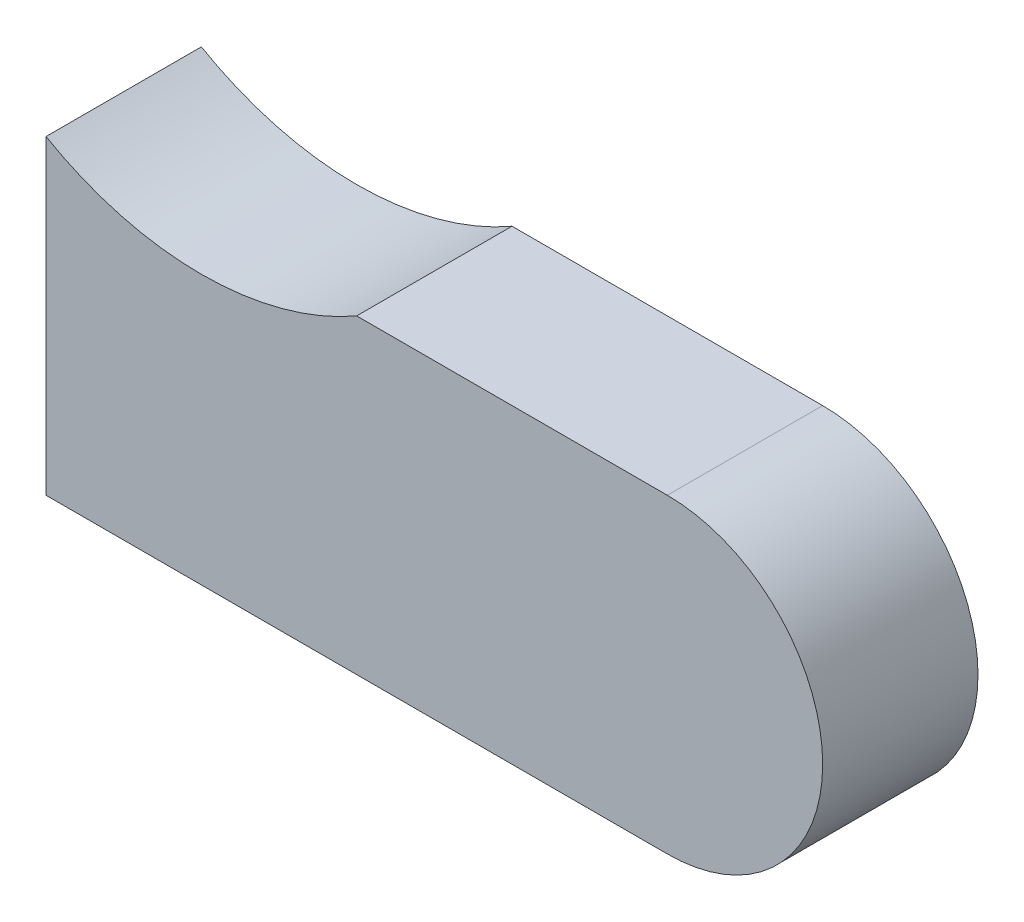
SolidWorks part; units mm, degrees
ref_plane "Front Plane" through (0, 0, 0) normal (0, 0, 1) x (1, 0, 0)
ref_plane "Top Plane" through (0, 0, 0) normal (0, 1, 0) x (1, 0, 0)
ref_plane "Right Plane" through (0, 0, 0) normal (1, 0, 0) x (0, 0, -1)
sketch "Sketch1" plane through (0, 0, 0) normal (0, 0, 1) x (1, 0, 0)
  line L0 (0, 0) -> (20, 0)
  line L1 (20, 10) -> (10, 10)
  line L2 (0, 10) -> (0, 0)
  arc A0 (20, 0) -> (20, 10) centre (20, 5) ccw
  arc A1 (10, 10) -> (0, 10) centre (5, 18.6603) cw
  dimension "D2" = 5
  dimension "D4" = 10
  dimension "D5" = 10
  dimension "D1" = 20
  dimension "D3" = 10
extrude "Boss-Extrude1" add sketch "Sketch1" along normal blind 5
